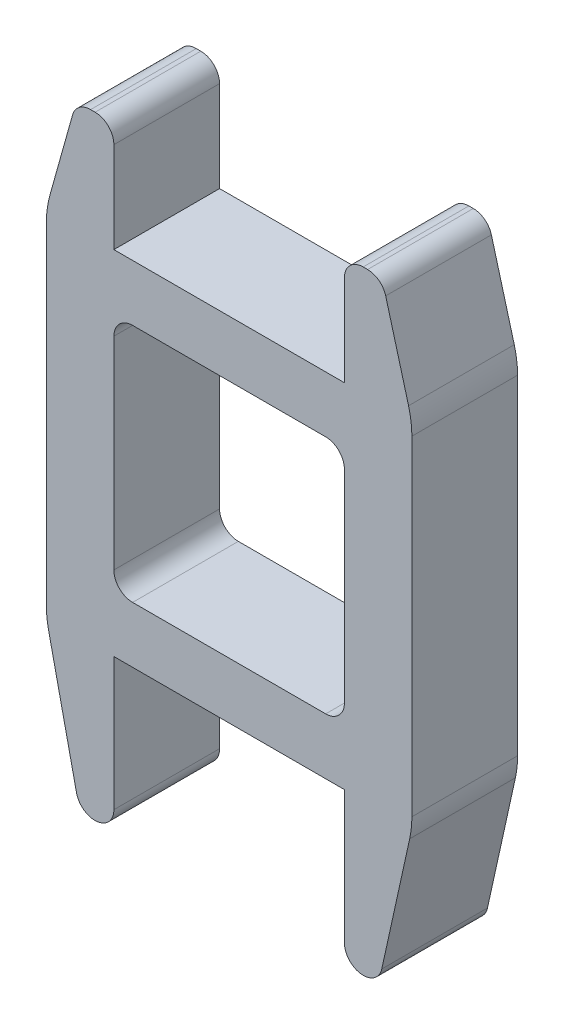
SolidWorks part; units mm, degrees
material "Acrylic (Medium-high impact)"
ref_plane "Front Plane" through (0, 0, 0) normal (0, 0, 1) x (1, 0, 0)
ref_plane "Top Plane" through (0, 0, 0) normal (0, 1, 0) x (1, 0, 0)
ref_plane "Right Plane" through (0, 0, 0) normal (1, 0, 0) x (0, 0, -1)
sketch "Sketch1" plane through (0, 0, 0) normal (0, 0, 1) x (1, 0, 0)
  line L0 (1247.2596, 961.2772) -> (1247.2596, 950.4772)
  line L1 (1263.1596, 947.9772) -> (1243.6596, 947.9772) construction
  line L2 (1247.2596, 946.4772) -> (1243.6596, 946.4772) construction
  line L3 (1248.2596, 962.2772) -> (1258.5596, 962.2772)
  line L4 (1246.0178, 971.1264) -> (1246.2596, 971.1264)
  line L5 (1247.2596, 970.1264) -> (1247.2596, 965.2772)
  line L6 (1247.2596, 955.8772) -> (1259.5596, 955.8772) construction
  line L7 (1259.5596, 965.2772) -> (1247.2596, 965.2772)
  line L8 (1243.6596, 964.7327) -> (1243.6596, 947.0217)
  line L9 (1243.7768, 945.9455) -> (1245.2674, 939.1828)
  line L10 (1247.2596, 965.2772) -> (1243.6596, 965.2772) construction
  line L11 (1259.5596, 946.4772) -> (1247.2596, 946.4772)
  line L12 (1243.8453, 966.0827) -> (1245.0549, 970.3964)
  line L13 (1247.2596, 939.398) -> (1247.2596, 946.4772)
  line L14 (1246.244, 938.398) -> (1246.2596, 938.398)
  line L15 (1248.2596, 949.4772) -> (1258.5596, 949.4772)
  line L16 (1259.5596, 965.2772) -> (1263.1596, 965.2772) construction
  line L17 (1259.5596, 946.4772) -> (1263.1596, 946.4772) construction
  line L18 (1260.5753, 938.398) -> (1260.5596, 938.398)
  line L19 (1253.4096, -39.6851) -> (1253.4096, 49960.3149) construction
  line L20 (1259.5596, 939.398) -> (1259.5596, 946.4772)
  line L21 (1262.9824, 965.9249) -> (1261.761, 970.3902)
  line L22 (1263.0424, 945.9455) -> (1261.5519, 939.1828)
  line L23 (1263.1596, 964.6057) -> (1263.1596, 947.0217)
  line L24 (1259.5596, 970.1264) -> (1259.5596, 965.2772)
  line L25 (1260.7964, 971.1264) -> (1260.5596, 971.1264)
  line L26 (1263.1596, 963.7772) -> (1243.6596, 963.7772) construction
  line L27 (1259.5596, 961.2772) -> (1259.5596, 950.4772)
  arc A0 (1248.2596, 949.4772) -> (1247.2596, 950.4772) centre (1248.2596, 950.4772) cw
  arc A1 (1258.5596, 949.4772) -> (1259.5596, 950.4772) centre (1258.5596, 950.4772) ccw
  arc A2 (1258.5596, 962.2772) -> (1259.5596, 961.2772) centre (1258.5596, 961.2772) cw
  arc A3 (1248.2596, 962.2772) -> (1247.2596, 961.2772) centre (1248.2596, 961.2772) ccw
  arc A4 (1246.244, 938.398) -> (1245.2674, 939.1828) centre (1246.244, 939.398) cw
  arc A5 (1246.2596, 938.398) -> (1247.2596, 939.398) centre (1246.2596, 939.398) ccw
  arc A6 (1260.5753, 938.398) -> (1261.5519, 939.1828) centre (1260.5753, 939.398) ccw
  arc A7 (1260.5596, 938.398) -> (1259.5596, 939.398) centre (1260.5596, 939.398) cw
  arc A8 (1261.761, 970.3902) -> (1260.7964, 971.1264) centre (1260.7964, 970.1264) ccw
  arc A9 (1260.5596, 971.1264) -> (1259.5596, 970.1264) centre (1260.5596, 970.1264) ccw
  arc A10 (1247.2596, 970.1264) -> (1246.2596, 971.1264) centre (1246.2596, 970.1264) ccw
  arc A11 (1246.0178, 971.1264) -> (1245.0549, 970.3964) centre (1246.0178, 970.1264) ccw
  arc A12 (1262.9824, 965.9249) -> (1263.1596, 964.6057) centre (1258.1596, 964.6057) cw
  arc A13 (1263.0424, 945.9455) -> (1263.1596, 947.0217) centre (1258.1596, 947.0217) ccw
  arc A14 (1243.7768, 945.9455) -> (1243.6596, 947.0217) centre (1248.6596, 947.0217) cw
  arc A15 (1243.6596, 964.7327) -> (1243.8453, 966.0827) centre (1248.6596, 964.7327) cw
  point P2 (1263.1596, 955.8772)
  point P14 (1243.6596, 955.8772)
  point P15 (1253.4096, 965.2772)
  point P20 (1253.4096, 963.7772)
  point P26 (1253.4096, 955.8772)
  point P28 (1253.4096, 965.2772)
  point P30 (1253.4096, 962.2772)
  point P31 (1253.4096, 947.9772)
  point P33 (1253.4096, 949.4772)
  point P36 (1253.4096, 946.4772)
  point P38 (1253.4096, 962.2772)
  point P41 (1247.2596, 949.4772)
  point P44 (1259.5596, 949.4772)
  point P47 (1259.5596, 962.2772)
  point P50 (1247.2596, 962.2772)
  point P53 (1245.4404, 938.398)
  point P56 (1247.2596, 938.398)
  point P59 (1261.3789, 938.398)
  point P62 (1259.5596, 938.398)
  point P65 (1261.5596, 971.1264)
  point P68 (1259.5596, 971.1264)
  point P71 (1247.2596, 971.1264)
  point P74 (1245.2596, 971.1264)
  dimension "D9" = 1
  dimension "D10" = 5
  dimension "D1" = 6.15
  dimension "D2" = 5.8492
  dimension "D3" = 2
  dimension "D4" = 3
  dimension "D5" = 9.4
  dimension "D6" = 8.0792
  dimension "D7" = 192.43
  dimension "D8" = 3.6
extrude "Boss-Extrude1" add sketch "Sketch1" along normal blind 5.64
